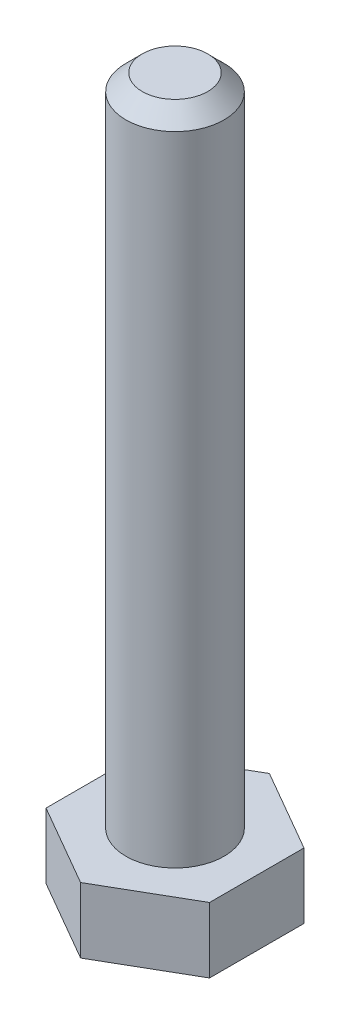
SolidWorks part; units mm, degrees
ref_plane "Front Plane" through (0, 0, 0) normal (0, 0, 1) x (1, 0, 0)
ref_plane "Top Plane" through (0, 0, 0) normal (0, 1, 0) x (1, 0, 0)
ref_plane "Right Plane" through (0, 0, 0) normal (1, 0, 0) x (0, 0, -1)
sketch "Sketch1" plane through (0, 0, 0) normal (0, 1, 0) x (1, 0, 0)
  line L1 (0, 5.7735) -> (-5, 2.8868)
  line L2 (-5, 2.8868) -> (-5, -2.8868)
  line L3 (-5, -2.8868) -> (0, -5.7735)
  line L4 (0, -5.7735) -> (5, -2.8868)
  line L5 (5, -2.8868) -> (5, 2.8868)
  line L6 (5, 2.8868) -> (0, 5.7735)
  circle A0 centre (0, 0) radius 5 construction
  dimension "D1" = 10
extrude "Boss-Extrude1" add sketch "Sketch1" along normal blind 4
sketch "Sketch2" plane through (0, 4, 0) normal (0, 1, 0) x (1, 0, 0)
  circle A0 centre (0, 0) radius 3
  dimension "D1" = 6
extrude "Boss-Extrude2" add sketch "Sketch2" along normal blind 40
chamfer "Chamfer1" distance 1 angle 45 1 edges at (0, 44, 3)
